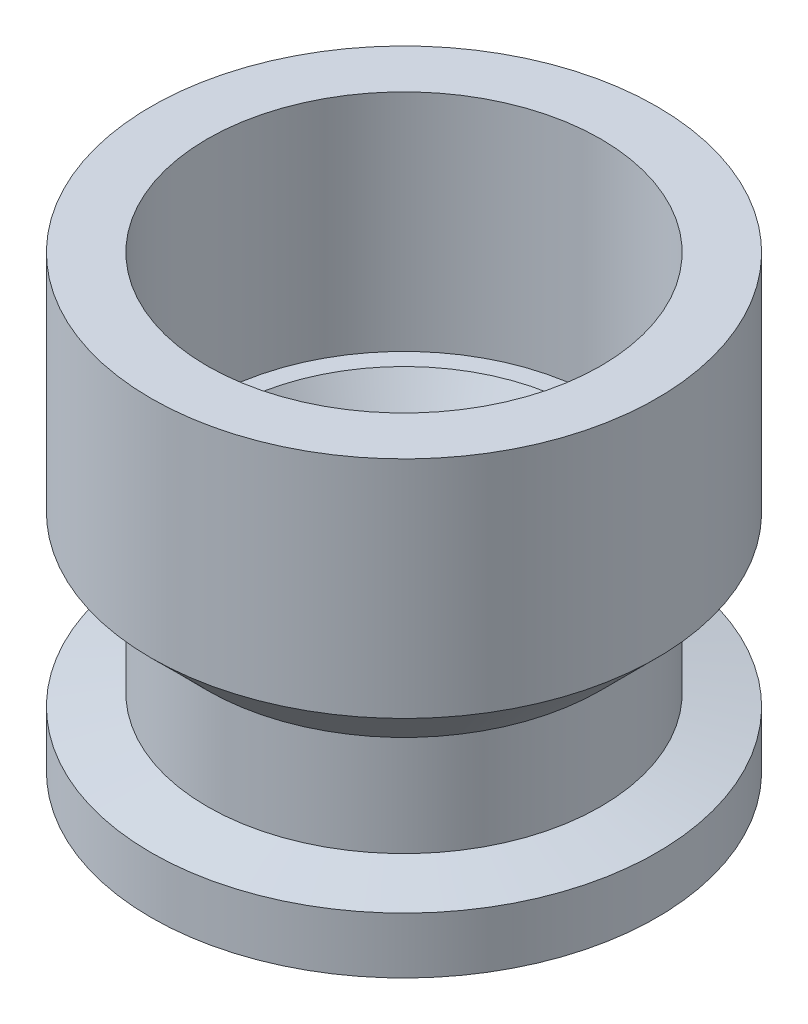
SolidWorks part; units mm, degrees
ref_plane "Front Plane" through (0, 0, 0) normal (0, 0, 1) x (1, 0, 0)
ref_plane "Top Plane" through (0, 0, 0) normal (0, 1, 0) x (1, 0, 0)
ref_plane "Right Plane" through (0, 0, 0) normal (1, 0, 0) x (0, 0, -1)
sketch "Sketch1" plane through (0, 0, 0) normal (0, 0, 1) x (1, 0, 0)
  line L0 (0, 0) -> (0, 8) construction
  line L1 (2, 0) -> (4.5, 0)
  line L2 (4.5, 0) -> (4.5, 1)
  line L3 (4.5, 8) -> (3.5, 8)
  line L4 (2, 2) -> (2, 0)
  line L6 (3.5, 8) -> (3.5, 4)
  line L7 (4.5, 4) -> (3.5, 3)
  line L8 (3.5, 3) -> (3.5, 1.2101)
  line L10 (4.5, 4) -> (4.5, 8)
  line L11 (4.5, 1) -> (3.5, 1.2101)
  line L12 (3.5, 4) -> (3.1711, 4)
  line L13 (3.1711, 4) -> (2, 2)
  dimension "D1" = 8
  dimension "D2" = 4.5
  dimension "D3" = 2.5
  dimension "D4" = 1
  dimension "D5" = 4
  dimension "D6" = 1
  dimension "D7" = 135
revolve "Revolve1" add sketch "Sketch1" angle 360 about L0
